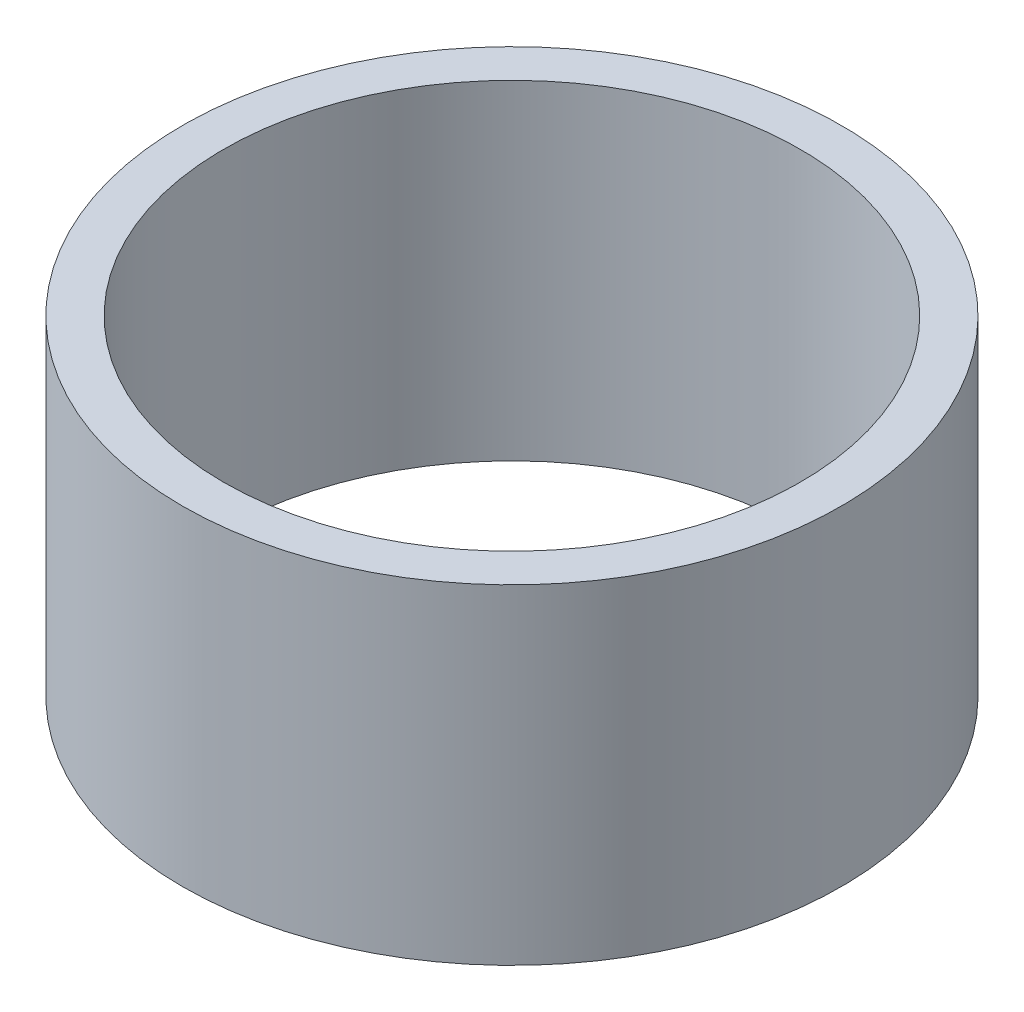
SolidWorks part; units mm, degrees
material "Nylon 101"
ref_plane "Front" through (0, 0, 0) normal (0, 0, 1) x (1, 0, 0)
ref_plane "Top" through (0, 0, 0) normal (0, 1, 0) x (1, 0, 0)
ref_plane "Right" through (0, 0, 0) normal (1, 0, 0) x (0, 0, -1)
sketch "Sketch1" plane through (0, 0, 0) normal (0, 1, 0) x (1, 0, 0)
  circle A0 centre (0, 0) radius 2
  circle A1 centre (0, 0) radius 1.75
  dimension "D1" = 4
  dimension "D2" = 3.5
extrude "Boss-Extrude1" add sketch "Sketch1" along normal blind 2
